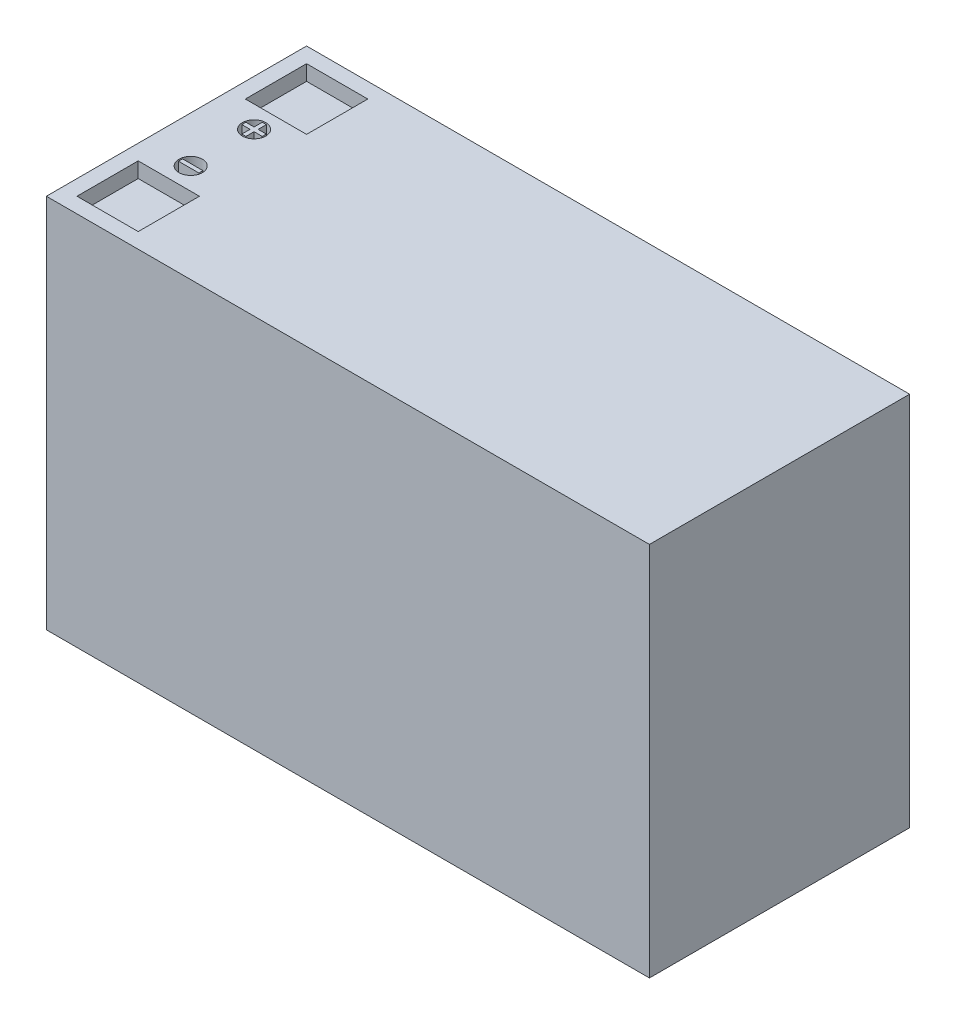
SolidWorks part; units mm, degrees
ref_plane "Front Plane" through (0, 0, 0) normal (0, 0, 1) x (1, 0, 0)
ref_plane "Top Plane" through (0, 0, 0) normal (0, 1, 0) x (1, 0, 0)
ref_plane "Right Plane" through (0, 0, 0) normal (1, 0, 0) x (0, 0, -1)
sketch "Sketch1" plane through (0, 0, 0) normal (0, 1, 0) x (1, 0, 0)
  line L1 (-71.4526, 38.2451) -> (78.6614, 38.2451)
  line L2 (-71.4526, 38.2451) -> (-71.4526, -26.5249)
  line L3 (-71.4526, -26.5249) -> (78.6614, -26.5249)
  line L4 (78.6614, 38.2451) -> (78.6614, -26.5249)
  dimension "D1" = 64.77
  dimension "D2" = 150.114
extrude "Boss-Extrude1" add sketch "Sketch1" along normal blind 93.472
sketch "Sketch2" plane through (0, 93.472, 0) normal (0, 1, 0) x (1, 0, 0)
  line L0 (-60.0226, -4.9404) -> (-60.0226, -4.9349)
  line L1 (-71.4526, 5.8601) -> (58.9596, 5.8601) construction
  line L2 (-67.6426, -22.7149) -> (-52.4026, -22.7149)
  line L3 (-71.4526, 38.2451) -> (-71.4526, -26.5249) construction
  line L4 (-60.0226, -1.5186) -> (-57.4826, -1.5186)
  line L5 (-60.0226, -1.5186) -> (-62.5626, -1.5186)
  line L6 (-67.6426, -22.7149) -> (-67.6426, -7.4749)
  line L7 (-67.6426, -7.4749) -> (-52.4026, -7.4749)
  line L8 (-52.4026, -22.7149) -> (-52.4026, -7.4749)
  line L9 (-62.5626, -1.5186) -> (-62.5626, -2.5346)
  line L10 (-62.5626, -2.5346) -> (-57.4826, -2.5346)
  line L11 (-57.4826, -1.5186) -> (-57.4826, -2.5346)
  line L12 (-57.4826, 13.2388) -> (-57.4826, 14.2548)
  line L13 (-59.516, 14.2548) -> (-57.4826, 14.2548)
  line L14 (-62.5626, 13.2388) -> (-62.5626, 14.2548)
  line L15 (-52.4026, 34.4351) -> (-52.4026, 19.1951)
  line L16 (-67.6426, 19.1951) -> (-52.4026, 19.1951)
  line L17 (-67.6426, 34.4351) -> (-67.6426, 19.1951)
  line L18 (-60.532, 13.2388) -> (-62.5626, 13.2388)
  line L19 (-59.516, 13.2388) -> (-57.4826, 13.2388)
  line L20 (-67.6426, 34.4351) -> (-52.4026, 34.4351)
  line L21 (-60.0226, 16.6607) -> (-60.0226, 16.6551)
  line L22 (-58.4993, 14.2548) -> (-59.516, 14.2548)
  line L23 (-60.532, 14.2548) -> (-60.532, 16.2868)
  line L24 (-62.5626, 14.2548) -> (-60.532, 14.2548)
  line L25 (-60.532, 16.2868) -> (-59.516, 16.2868)
  line L26 (-59.516, 16.2868) -> (-59.516, 14.2548)
  line L27 (-60.532, 13.2388) -> (-60.532, 11.2068)
  line L28 (-60.532, 11.2068) -> (-59.516, 11.2068)
  line L29 (-59.516, 13.2388) -> (-59.516, 11.2068)
  circle A0 centre (-60.0226, -2.0266) radius 2.9139
  circle A1 centre (-60.0226, 13.7468) radius 2.9139
  dimension "D1" = 15.24
  dimension "D2" = 0.508
  dimension "D3" = 15.24
  dimension "D4" = 2.9083
  dimension "D5" = 2.032
  dimension "D6" = 2.54
  dimension "D7" = 2.54
  dimension "D8" = 1.016
  dimension "D9" = 1.016
  dimension "D10" = 5.08
  dimension "D11" = 3.048
extrude "Cut-Extrude1" cut sketch "Sketch2" against normal blind 3.81
